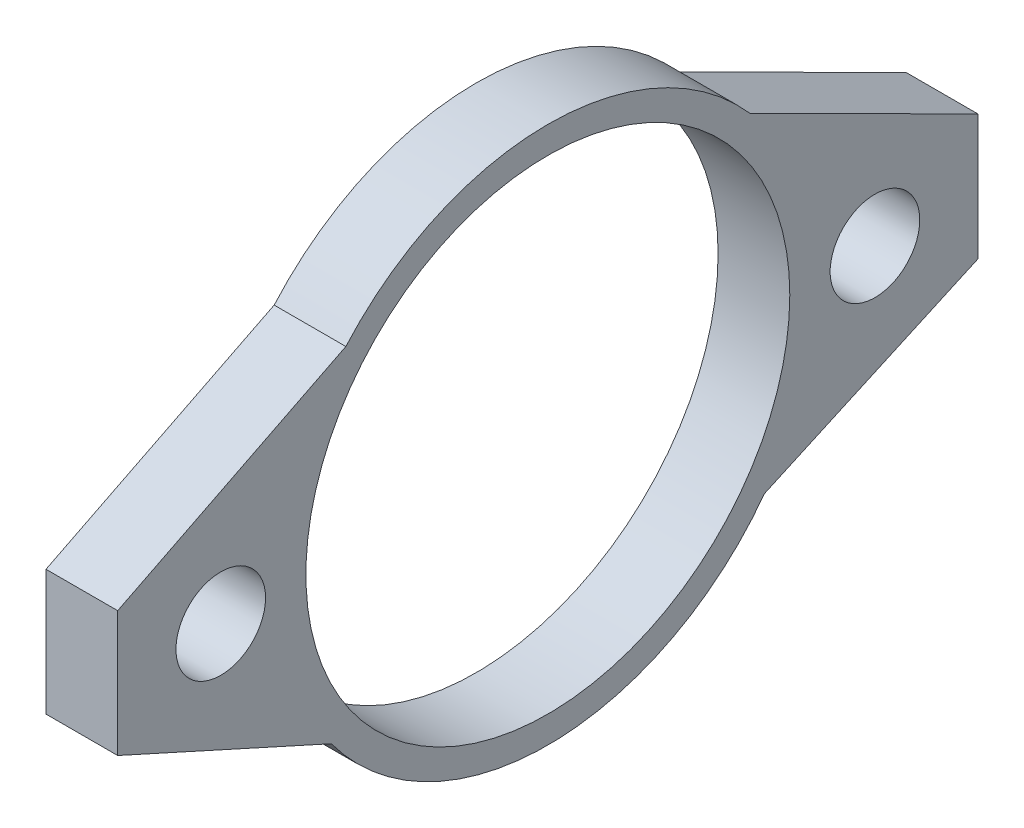
SolidWorks part; units mm, degrees
ref_plane "Alzado" through (0, 0, 0) normal (0, 0, 1) x (1, 0, 0)
ref_plane "Planta" through (0, 0, 0) normal (0, 1, 0) x (1, 0, 0)
ref_plane "Vista lateral" through (0, 0, 0) normal (1, 0, 0) x (0, 0, -1)
sketch "Croquis1" plane through (0, 0, 0) normal (1, 0, 0) x (0, 0, -1)
  line L0 (0, 15) -> (0, -15) construction
  line L1 (-24, 0) -> (24, 0) construction
  line L2 (-24, 3.5) -> (-24, -3.5)
  line L3 (24, 3.5) -> (24, -3.5)
  line L4 (-24, 3.5) -> (-11.2697, 9.8991)
  line L5 (11.2697, 9.8991) -> (24, 3.5)
  line L6 (-24, -3.5) -> (-12.0816, -8.8901)
  line L7 (12.0816, -8.8901) -> (24, -3.5)
  arc A0 (-12.0816, -8.8901) -> (12.0816, -8.8901) centre (0, 0) ccw
  circle A1 centre (-18.25, 0) radius 2.5
  circle A2 centre (18.25, 0) radius 2.5
  arc A3 (11.2697, 9.8991) -> (-11.2697, 9.8991) centre (0, 0) ccw
  circle A4 centre (0, 0) radius 13.5
  dimension "D1" = 30
  dimension "D2" = 5
  dimension "D3" = 5
  dimension "D10" = 27
  dimension "D4" = 18.25
  dimension "D5" = 18.25
  dimension "D6" = 48
  dimension "D7" = 24
  dimension "D8" = 7
  dimension "D9" = 7
  dimension "D11" = 3.5
extrude "Saliente-Extruir1" add sketch "Croquis1" along normal blind 4
